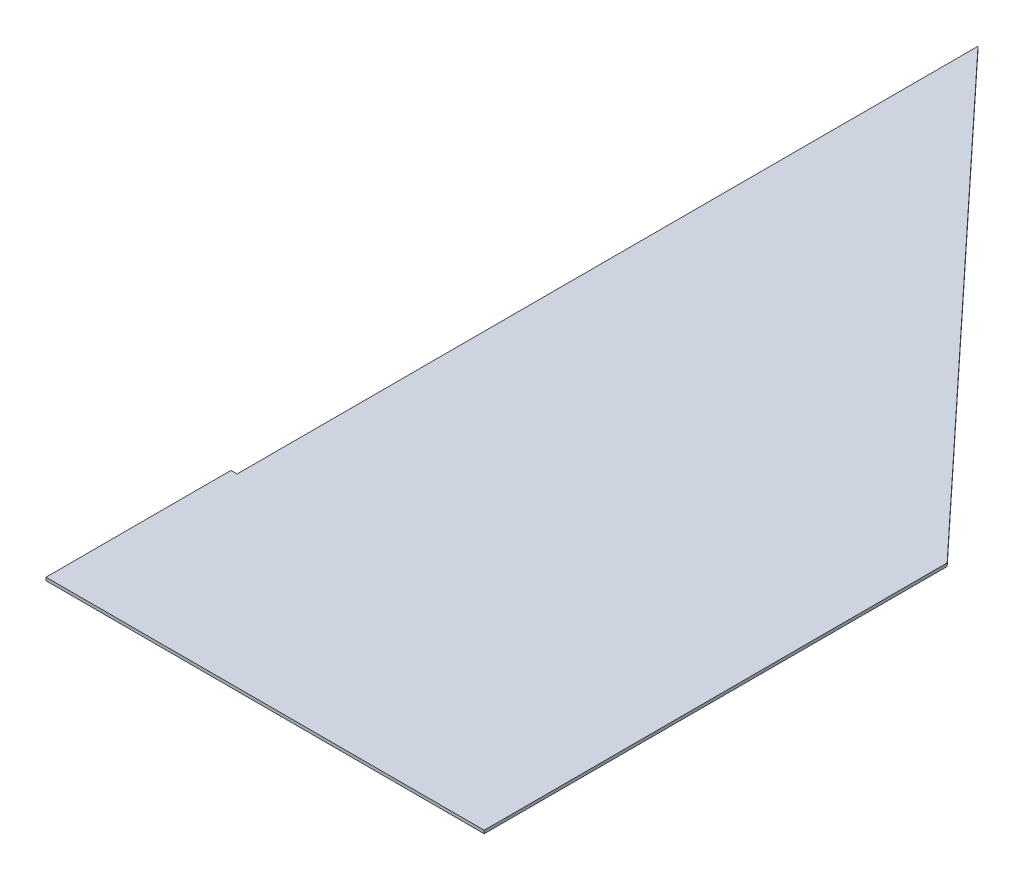
SolidWorks part; units mm, degrees
material "Fibra di Carbonio"
ref_plane "Piano frontale" through (0, 0, 0) normal (0, 0, 1) x (1, 0, 0)
ref_plane "Piano superiore" through (0, 0, 0) normal (0, 1, 0) x (1, 0, 0)
ref_plane "Piano destro" through (0, 0, 0) normal (1, 0, 0) x (0, 0, -1)
sketch "Forma aletta" plane through (0, 0, 0) normal (0, 1, 0) x (1, 0, 0)
  line L0 (0, 0) -> (0, 300) construction
  line L1 (0, 300) -> (0, 59.93)
  line L2 (0, 0) -> (140, 0)
  line L3 (140, 0) -> (140, 150)
  line L4 (140, 150) -> (0, 300)
  line L5 (0, 0) -> (-2, 0)
  line L6 (-2, 0) -> (-2, 59.93)
  line L7 (-2, 59.93) -> (0, 59.93)
  line L8 (-146, 59.93) -> (0, 59.93) construction
  line L9 (-146, 59.93) -> (0, 59.93) construction
  dimension "D1" = 300
  dimension "D2" = 2
  dimension "D3" = 205.1828
  dimension "D6" = 140
extrude "Estrusione-Estrusione1" add sketch "Forma aletta" along normal blind 1
